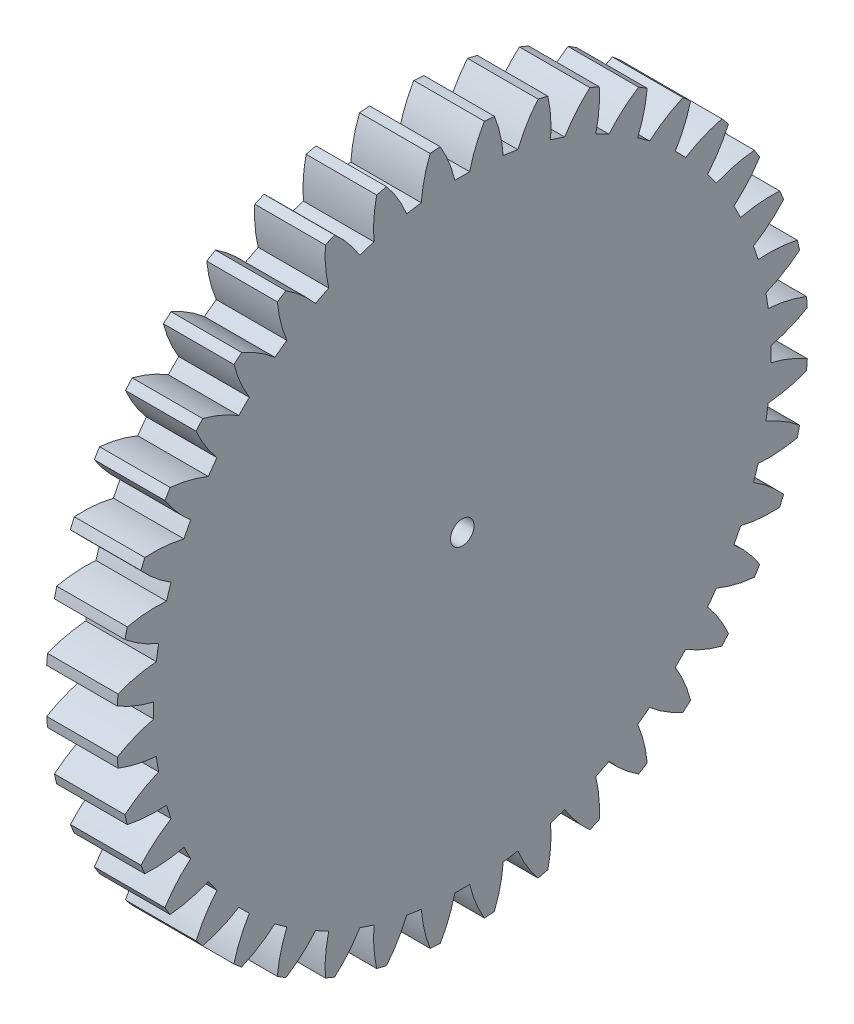
SolidWorks part; units mm, degrees
ref_plane "Plane1" through (0, 0, 0) normal (0, 0, 1) x (1, 0, 0)
ref_plane "Plane2" through (0, 0, 0) normal (0, 1, 0) x (1, 0, 0)
ref_plane "Plane3" through (0, 0, 0) normal (1, 0, 0) x (0, 0, -1)
other "Configuration Table"
sketch "HoldingSke" plane through (0, 0, 0) normal (0, 1, 0) x (1, 0, 0)
  line L0 (0, 0) -> (1.0943, -0.9183)
  line L1 (-15, 0) -> (100, 0) construction
  line L2 (0, 0) -> (-2.1039, 2.3779)
  line L3 (0, 0) -> (-11.863, 4.5341)
  line L4 (0, 0) -> (6.6156, 5.5511)
  line L5 (0, 0) -> (-46.8476, -17.4728)
  line L6 (0, 0) -> (-2.4869, -1.6779)
  line L7 (-2.1039, 2.3779) -> (8.6586, 51.2059)
  line L8 (-76.2, 54.61) -> (-76.1, 54.61)
  line L9 (-71.009, 38.7566) -> (-53.1078, 45.2721)
  line L10 (-76.2, 71.12) -> (104.1128, 71.12)
  line L11 (0, 0) -> (-3, 0)
  line L12 (-76.2, 101.6) -> (-76.173, 101.6)
  line L13 (24.9733, 27.94) -> (52.9518, 28.4284)
  line L14 (24.9733, 27.94) -> (24.9743, 27.94)
  line L15 (24.9733, 27.94) -> (100.4006, 29.5858)
  line L16 (-63.627, -0.7) -> (-12.827, -0.7)
  circle A0 centre (0, 0) radius 0.5
  circle A1 centre (0, 0) radius 13.124
  circle A2 centre (0, 0) radius 37.5
  circle A3 centre (0, 0) radius 0.5
  dimension "MHD" = 26.248
  dimension "Hub_dia" = 75
  dimension "Bore" = 1
  dimension "MBD" = 1
  dimension "Num_teeth" = 40
  dimension "Pitch" = 1.4286
  dimension "Overall_len" = 50
  dimension "Show_teeth" = 40
  dimension "Thickness" = 3
  dimension "OAL" = 50.0001
  dimension "T_dim" = 0.1
  dimension "Ap" = 20
  dimension "H" = 19.05
  dimension "Pitch_radius" = 180.3128
  dimension "Width" = 3
  dimension "Backlash" = 0.027
  dimension "Addendum_fac" = 1
  dimension "Dedendum_fac" = 1.25
  dimension "Clearance_fac" = 0.25
  dimension "Dedendum_add" = 0.001
  dimension "Module" = 0.7
sketch "BasProSke" plane through (0, 0, 0) normal (0, 1, 0) x (1, 0, 0)
  line L0 (-10, 0) -> (60, 0) construction
  line L1 (0, 0) -> (0, 14.7)
  line L2 (0, 0) -> (3, 0)
  line L3 (3, 0) -> (3, 14.7)
  line L4 (3, 14.7) -> (0, 14.7)
  dimension "Thickness" = 3
  dimension "Diameter" = 29.4
revolve "Base-Revolve" add sketch "BasProSke" angle 360 about L0
sketch "TooCutSke" plane through (0, 0, 0) normal (1, 0, 0) x (0, 0, -1)
  line L1 (0, 0) -> (0, 107) construction
  line L2 (0, 0) -> (-0.5969, 13.9873) construction
  line L3 (0, 0) -> (-2.1954, 27.8957) construction
  line L4 (-0.5969, 13.9873) -> (-1.0977, 13.9479) construction
  arc A0 (0.3147, 13.1202) -> (-0.3147, 13.1202) centre (0, 0) ccw
  arc A1 (0.9534, 14.6945) -> (-0.9534, 14.6945) centre (0, 0) ccw
  circle A2 centre (0, 0) radius 14 construction
  circle A3 centre (0, 0) radius 13.1557 construction
  arc A4 (-0.3147, 13.1202) -> (-0.9534, 14.6945) centre (-5.7631, 11.8262) ccw
  arc A5 (0.9534, 14.6945) -> (0.3147, 13.1202) centre (5.7631, 11.8262) ccw
  dimension "Root_dia" = 26.248
  dimension "Overcut_dia" = 29.4508
  dimension "Pitch_dia" = 28
  dimension "Base_dia" = 26.3114
  dimension "Flank_rad" = 5.6
  dimension "Half_ang" = 4.5
  dimension "Half_CT" = 0.5024
extrude "ToothCut" cut sketch "TooCutSke" along normal through all
fillet "Breaks" [suppressed] radius 0.014
fillet "RootFillets" [suppressed] radius 0.176
pattern_circular "TeethCuts" count 40 every 9 about axis through (-10, 0, 0) along (1, 0, 0) of "ToothCut", "RootFillets", "Breaks"
sketch "HubNeaOneSke" plane through (0, 0, 0) normal (-1, 0, 0) x (0, 0, 1)
  circle A0 centre (0, 0) radius 13.124
  dimension "Diameter" = 26.248
extrude "HubNearOne" [suppressed] add sketch "HubNeaOneSke" along normal blind 47.0001
sketch "HubNeaBotSke" plane through (0, 0, 0) normal (-1, 0, 0) x (0, 0, 1)
  circle A0 centre (0, 0) radius 13.124
  dimension "Diameter" = 26.248
extrude "HubNearBoth" [suppressed] add sketch "HubNeaBotSke" along normal blind 23.5
ref_plane "FarPln" through (3, 0, 0) normal (1, 0, 0) x (0, 0, -1)
sketch "HubFarSke" plane through (3, 0, 0) normal (1, 0, 0) x (0, 0, -1)
  circle A0 centre (0, 0) radius 13.124
  dimension "Diameter" = 26.248
extrude "HubFar" [suppressed] add sketch "HubFarSke" along normal blind 23.5
sketch "BorSke" plane through (0, 0, 0) normal (1, 0, 0) x (0, 0, -1)
  circle A0 centre (0, 0) radius 0.5
  dimension "Diameter" = 1
extrude "Bore" cut sketch "BorSke" along normal mid plane 100.0001
sketch "KeySke" plane through (0, 0, 0) normal (1, 0, 0) x (0, 0, -1)
  line L0 (-0.05, 0) -> (-0.05, 0.6)
  line L1 (-0.05, 0.6) -> (0.05, 0.6)
  line L2 (0.05, 0.6) -> (0.05, 0)
  line L3 (0, 0) -> (0, 34) construction
  line L4 (-0.05, 0) -> (0.05, 0)
  dimension "Offset" = 0.6
  dimension "Width" = 0.1
extrude "Keyway" [suppressed] cut sketch "KeySke" along normal mid plane 100.0001
pattern_circular "Keyway2" [suppressed] count 2 every 90 about axis through (-10, 0, 0) along (1, 0, 0)
equation "' \"Module@HoldingSke\" = 6.35"
equation "' \"Num_teeth@HoldingSke\" = 12"
equation "' \"Ap@HoldingSke\" =  20"
equation "' \"Ap@HoldingSke\" = 20"
equation "' \"Width@HoldingSke\" = 0.5 * 25.4"
equation "' \"Hub_dia@HoldingSke\"= 1 * 25.4"
equation "' \"Hub_dia@HoldingSke\" = 1 * 25.4"
equation "' \"Overall_len@HoldingSke\" = 1.0 * 25.4"
equation "' \"Bore@HoldingSke\" = 0.75 * 25.4"
equation "' \"T_dim@HoldingSke\" = 0.1 * 25.4"
equation "' \"Width@KeySke\" = 0.25 * 25.4"
equation "' \"Show_teeth@HoldingSke\" = 13"
equation "' \"Backlash@HoldingSke\" = 0.009 * 25.4"
equation "' \"Addendum_fac@HoldingSke\" = 1.0"
equation "' \"Dedendum_fac@HoldingSke\" = 1.25"
equation "' \"Dedendum_add@HoldingSke\" = 0.00005 * 25.4"
equation "' \"Clearance_fac@HoldingSke\" = 0.25"
equation "\"Pitch@HoldingSke\" = 1 / \"Module@HoldingSke\""
equation "\"Overcut_dia@TooCutSke\" = (\"Num_teeth@HoldingSke\" + 2 * \"Addendum_fac@HoldingSke\") / \"Pitch@HoldingSke\" + 0.002 * 25.4"
equation "\"Pitch_dia@TooCutSke\" = \"Num_teeth@HoldingSke\" / \"Pitch@HoldingSke\""
equation "\"Base_dia@TooCutSke\" = \"Num_teeth@HoldingSke\" / \"Pitch@HoldingSke\" * cos((\"Ap@HoldingSke\"  * 3.14159265 / 180))"
equation "\"Root_dia@TooCutSke\" = (\"Num_teeth@HoldingSke\" + 2) / \"Pitch@HoldingSke\" - 2 * (\"Addendum_fac@HoldingSke\" + \"Dedendum_fac@HoldingSke\") / \"Pitch@HoldingSke\" - \"Dedendum_add@HoldingSke\" * 2"
equation "\"Half_ang@TooCutSke\" = 180 / \"Num_teeth@HoldingSke\""
equation "\"Half_CT@TooCutSke\" = \"Num_teeth@HoldingSke\" / \"Pitch@HoldingSke\" * sin((3.14159265 / 2 / \"Num_teeth@HoldingSke\")) / 2 - 7 * \"Backlash@HoldingSke\" / 4"
equation "\"Flank_rad@TooCutSke\" = \"Num_teeth@HoldingSke\" / \"Pitch@HoldingSke\" / 5"
equation "\"Radius@RootFillets\" = \"Clearance_fac@HoldingSke\" / \"Pitch@HoldingSke\" + \"Dedendum_add@HoldingSke\""
equation "\"Break_rad@Breaks\" = 0.02 / \"Pitch@HoldingSke\""
equation "\"Thickness@HoldingSke\" = \"Width@HoldingSke\""
equation "\"OAL@HoldingSke\" = \"Thickness@HoldingSke\""
equation "\"MHD@HoldingSke\" = (\"Num_teeth@HoldingSke\" + 2) / \"Pitch@HoldingSke\" - 2 * (\"Addendum_fac@HoldingSke\" + \"Dedendum_fac@HoldingSke\")  / \"Pitch@HoldingSke\" - \"Dedendum_add@HoldingSke\" * 2"
equation "\"MBD@HoldingSke\" = (\"Num_teeth@HoldingSke\" + 2) / \"Pitch@HoldingSke\" - 2 * (\"Addendum_fac@HoldingSke\" + \"Dedendum_fac@HoldingSke\")  / \"Pitch@HoldingSke\" - \"Dedendum_add@HoldingSke\" * 2 - 0.002 * 25.4"
equation "\"MHD@HoldingSke\" = ((sgn( \"MHD@HoldingSke\" - \"Hub_dia@HoldingSke\" )-1)*( \"MHD@HoldingSke\" - \"Hub_dia@HoldingSke\" ))/-2+ \"Hub_dia@HoldingSke\""
equation "\"MBD@HoldingSke\" = ((sgn( \"MBD@HoldingSke\" - \"Bore@HoldingSke\" )-1)*( \"MBD@HoldingSke\" - \"Bore@HoldingSke\" ))/-2+ \"Bore@HoldingSke\""
equation "\"OAL@HoldingSke\" = ((sgn( \"OAL@HoldingSke\" - \"Overall_len@HoldingSke\" )+1)*( \"OAL@HoldingSke\" - \"Overall_len@HoldingSke\" ))/2 + \"Overall_len@HoldingSke\" + 0.000002 * 25.4"
equation "\"Num_teeth@TeethCuts\" = int( \"Show_teeth@HoldingSke\" ) + 1"
equation "\"Num_teeth@TeethCuts\" = ((sgn( \"Num_teeth@TeethCuts\" - \"Num_teeth@HoldingSke\" )-1)*( \"Num_teeth@TeethCuts\" - \"Num_teeth@HoldingSke\" ))/-2+ \"Num_teeth@HoldingSke\""
equation "\"Num_teeth@TeethCuts\" = ((sgn( \"Num_teeth@TeethCuts\" - 2.0)+1)*( \"Num_teeth@TeethCuts\" - 2.0))/2 +2.0"
equation "\"Angle@TeethCuts\" = 360.0 / \"Num_teeth@HoldingSke\""
equation "\"Diameter@BasProSke\" = (\"Num_teeth@HoldingSke\" + 2 * \"Addendum_fac@HoldingSke\") / \"Pitch@HoldingSke\""
equation "\"Thickness@BasProSke\"  = \"Thickness@HoldingSke\""
equation "' \"Fillet_rad@BasProSke\" =  \"Thickness@HoldingSke\" * 0.05"
equation "' \"Fillet_rad@BasProSke\" = \"Thickness@HoldingSke\" * 0.05"
equation "\"MHD@HoldingSke\" = ((sgn( \"MHD@HoldingSke\" - \"Root_dia@TooCutSke\" )-1)*( \"MHD@HoldingSke\" - \"Root_dia@TooCutSke\" ))/-2+ \"Root_dia@TooCutSke\""
equation "\"Diameter@HubNeaOneSke\" = \"MHD@HoldingSke\""
equation "\"Length@HubNearOne\" = \"OAL@HoldingSke\" - \"Thickness@BasProSke\""
equation "\"Diameter@HubNeaBotSke\" = \"MHD@HoldingSke\""
equation "\"Length@HubNearBoth\" = ( \"OAL@HoldingSke\" - \"Thickness@BasProSke\" ) / 2.0"
equation "\"Thickness@FarPln\" = \"Thickness@BasProSke\""
equation "\"Diameter@HubFarSke\" = \"MHD@HoldingSke\""
equation "\"Length@HubFar\" = ( \"OAL@HoldingSke\" - \"Thickness@BasProSke\" ) / 2.0"
equation "\"Diameter@BorSke\" = \"MBD@HoldingSke\""
equation "\"D1@Bore\" = \"OAL@HoldingSke\" * 2.0"
equation "\"D1@Keyway\" = \"OAL@HoldingSke\" * 2.0"
equation "\"Offset@KeySke\" = \"T_dim@HoldingSke\" + \"MBD@HoldingSke\" / 2.0"
